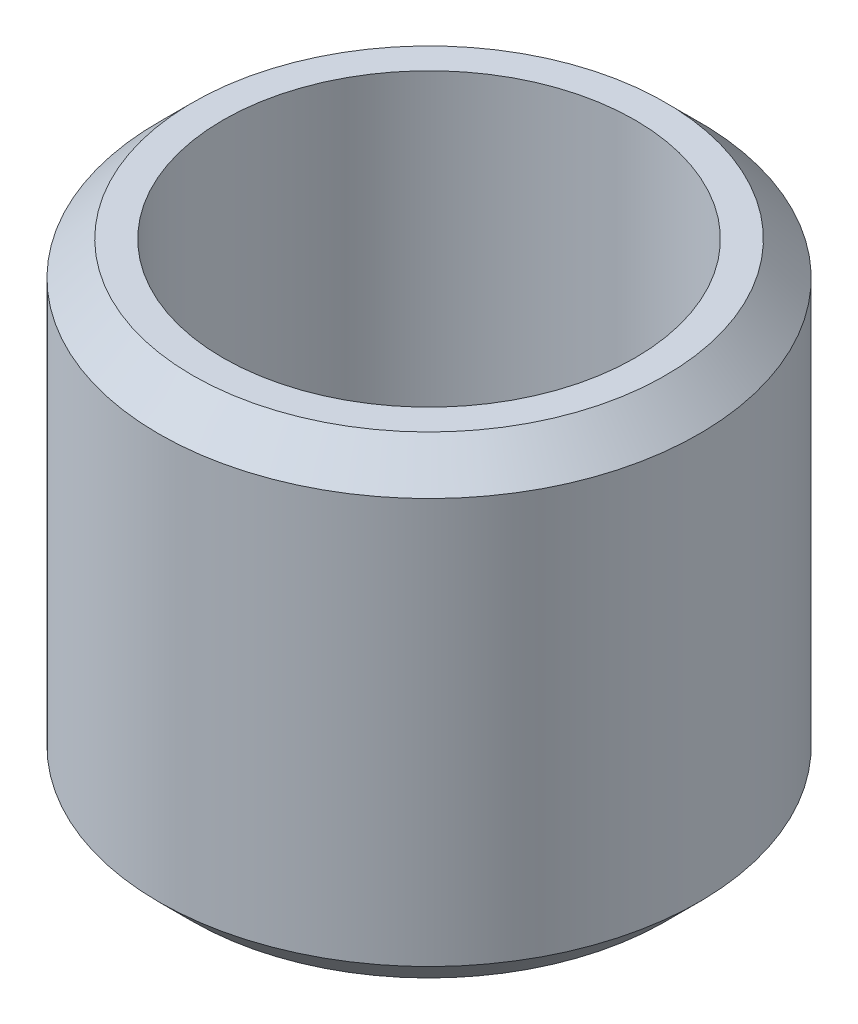
SolidWorks part; units mm, degrees
ref_plane "Front Plane" through (0, 0, 0) normal (0, 0, 1) x (1, 0, 0)
ref_plane "Top Plane" through (0, 0, 0) normal (0, 1, 0) x (1, 0, 0)
ref_plane "Right Plane" through (0, 0, 0) normal (1, 0, 0) x (0, 0, -1)
sketch "Sketch1" plane through (0, 0, 0) normal (0, 1, 0) x (1, 0, 0)
  circle A0 centre (0, 0) radius 4
  circle A1 centre (0, 0) radius 3.05 construction
  dimension "D1" = 8
  dimension "D2" = 6.1
extrude "Boss-Extrude1" add sketch "Sketch1" along normal blind 7
sketch "Sketch2" plane through (0, 7, 0) normal (0, 1, 0) x (1, 0, 0)
  circle A0 centre (0, 0) radius 3.05 construction
  circle A1 centre (0, 0) radius 3.05
extrude "Cut-Extrude1" cut sketch "Sketch2" against normal blind 6
chamfer "Chamfer1" distance 0.5 angle 45 2 edges at (0, 0, 4) (0, 7, 4)
